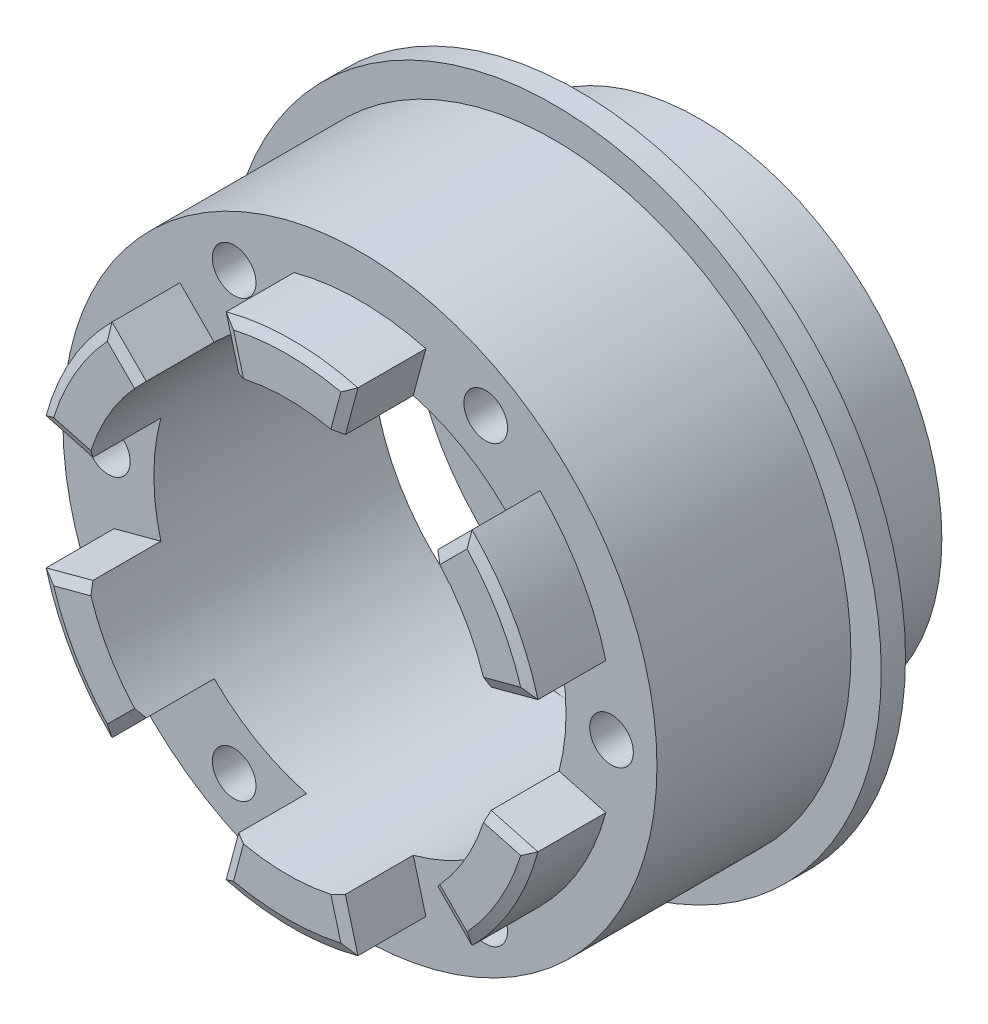
SolidWorks part; units mm, degrees
ref_plane "정면" through (0, 0, 0) normal (0, 0, 1) x (1, 0, 0)
ref_plane "윗면" through (0, 0, 0) normal (0, 1, 0) x (1, 0, 0)
ref_plane "우측면" through (0, 0, 0) normal (1, 0, 0) x (0, 0, -1)
sketch "스케치1" plane through (0, 0, 0) normal (0, 0, 1) x (1, 0, 0)
  circle A0 centre (0, 0) radius 10
  dimension "D1" = 20
extrude "보스-돌출1" add sketch "스케치1" along normal blind 2
sketch "스케치2" plane through (0, 0, 2) normal (0, 0, 1) x (1, 0, 0)
  circle A0 centre (0, 0) radius 10
  circle A1 centre (0, 0) radius 8.5
  circle A5 centre (0, 0) radius 10 construction
  dimension "D1" = 1.5
extrude "보스-돌출2" add sketch "스케치2" along normal blind 3
sketch "스케치4" plane through (0, 0, 5) normal (0, 0, 1) x (1, 0, 0)
  circle A0 centre (0, 0) radius 13.5
  circle A1 centre (0, 0) radius 8.5
  circle A2 centre (0, 0) radius 8.5 construction
  dimension "D1" = 27
extrude "보스-돌출3" add sketch "스케치4" along normal blind 1
sketch "스케치5" plane through (0, 0, 6) normal (0, 0, 1) x (1, 0, 0)
  circle A0 centre (0, 0) radius 8.5
  circle A1 centre (0, 0) radius 12.25
  circle A2 centre (0, 0) radius 8.5 construction
  dimension "D1" = 24.5
extrude "보스-돌출4" add sketch "스케치5" along normal blind 8
sketch "스케치6" plane through (0, 0, 14) normal (0, 0, 1) x (1, 0, 0)
  circle A0 centre (0, 0) radius 10.375 construction
  circle A6 centre (0, 0) radius 8.5 construction
  circle A8 centre (10.375, 0) radius 0.9
  circle A9 centre (5.1875, -8.985) radius 0.9
  circle A10 centre (-5.1875, -8.985) radius 0.9
  circle A11 centre (-10.375, 0) radius 0.9
  circle A12 centre (-5.1875, 8.985) radius 0.9
  circle A13 centre (5.1875, 8.985) radius 0.9
  point P19 (0, 0)
  point P20 (0, 0)
  dimension "D1" = 1.875
  dimension "D2" = 1.8
  dimension "D3" = 6
extrude "컷-돌출1" cut sketch "스케치6" against normal blind 8
sketch "스케치7" plane through (0, 0, 0) normal (0, 0, -1) x (-1, 0, 0)
  circle A0 centre (0, 0) radius 7 construction
  circle A5 centre (0, 0) radius 3
  circle A6 centre (-7, 0) radius 1.15
  circle A7 centre (7, 0) radius 1.15
  circle A9 centre (0, 7) radius 1.15
  circle A11 centre (0, -7) radius 1.15
  dimension "D1" = 14
  dimension "D2" = 2.3
  dimension "D4" = 6
extrude "컷-돌출2" cut sketch "스케치7" against normal through all
sketch "스케치9" plane through (0, 0, 0) normal (1, 0, 0) x (0, 0, -1)
  line L0 (-5, -10) -> (-5, 10) construction
  line L1 (-5, -8.5) -> (-2, -8.5)
  line L2 (-5, -8.5) -> (-5, 8.5)
  line L3 (-5, 8.5) -> (-2, 8.5)
  line L4 (-2, -8.5) -> (-2, 8.5)
  line L5 (0, 10) -> (-5, 10) construction
  line L6 (-5, -10) -> (0, -10) construction
  line L7 (0, -10) -> (0, 10) construction
  dimension "D1" = 1.5
  dimension "D2" = 1.5
  dimension "D3" = 2
extrude "컷-돌출4" cut sketch "스케치9" against normal through all
sketch "스케치10" plane through (0, 0, 14) normal (0, 0, 1) x (1, 0, 0)
  line L1 (2.2, 8.2104) -> (2.7176, 10.1422)
  line L3 (6.0104, 6.0104) -> (7.4246, 7.4246)
  line L5 (8.2104, 2.2) -> (10.1422, 2.7176)
  line L7 (8.2104, -2.2) -> (10.1422, -2.7176)
  line L9 (6.0104, -6.0104) -> (7.4246, -7.4246)
  line L11 (2.2, -8.2104) -> (2.7176, -10.1422)
  line L13 (-2.2, -8.2104) -> (-2.7176, -10.1422)
  line L15 (-6.0104, -6.0104) -> (-7.4246, -7.4246)
  line L17 (-8.2104, -2.2) -> (-10.1422, -2.7176)
  line L19 (-8.2104, 2.2) -> (-10.1422, 2.7176)
  line L21 (-6.0104, 6.0104) -> (-7.4246, 7.4246)
  line L23 (-2.2, 8.2104) -> (-2.7176, 10.1422)
  arc A0 (-7.4246, 7.4246) -> (-10.1422, 2.7176) centre (0, 0) ccw
  arc A1 (-8.2104, -2.2) -> (-6.0104, -6.0104) centre (0, 0) ccw
  arc A2 (2.7176, 10.1422) -> (-2.7176, 10.1422) centre (0, 0) ccw
  arc A3 (10.1422, 2.7176) -> (7.4246, 7.4246) centre (0, 0) ccw
  arc A4 (7.4246, -7.4246) -> (10.1422, -2.7176) centre (0, 0) ccw
  arc A5 (-2.7176, -10.1422) -> (2.7176, -10.1422) centre (0, 0) ccw
  arc A6 (-10.1422, -2.7176) -> (-7.4246, -7.4246) centre (0, 0) ccw
  arc A7 (-2.2, -8.2104) -> (2.2, -8.2104) centre (0, 0) ccw
  arc A8 (6.0104, -6.0104) -> (8.2104, -2.2) centre (0, 0) ccw
  arc A9 (8.2104, 2.2) -> (6.0104, 6.0104) centre (0, 0) ccw
  arc A10 (2.2, 8.2104) -> (-2.2, 8.2104) centre (0, 0) ccw
  arc A11 (-6.0104, 6.0104) -> (-8.2104, 2.2) centre (0, 0) ccw
  circle A12 centre (0, 0) radius 8.5 construction
  arc A13 (0, -8.5) -> (0, 8.5) centre (0, 0) ccw construction
  point P30 (0, 0)
  dimension "D1" = 2
extrude "보스-돌출5" add sketch "스케치10" along normal blind 3
chamfer "모따기1" distance 0.2 angle 64 18 edges at (-9.1763, -2.4588, 17) (-6.7175, -6.7175, 17) (-2.4588, -9.1763, 17) (2.4588, -9.1763, 17) (6.7175, -6.7175, 17) (9.1763, -2.4588, 17) (9.1763, 2.4588, 17) (6.7175, 6.7175, 17) (2.4588, 9.1763, 17) (-2.4588, 9.1763, 17) (-6.7175, 6.7175, 17) (-9.1763, 2.4588, 17) (-9.0933, -5.25, 17) (0, -10.5, 17) (9.0933, -5.25, 17) (9.0933, 5.25, 17) (0, 10.5, 17) (-9.0933, 5.25, 17)
